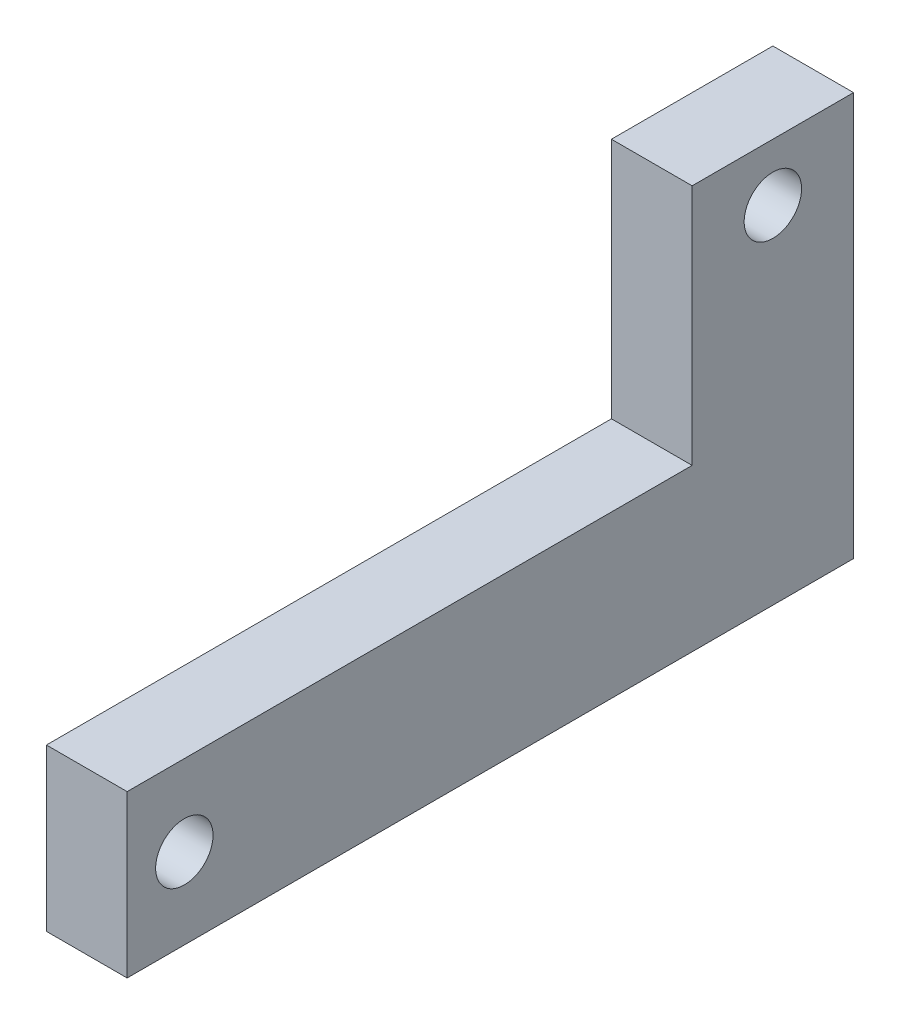
SolidWorks part; units mm, degrees
ref_plane "Front Plane" through (0, 0, 0) normal (0, 0, 1) x (1, 0, 0)
ref_plane "Top Plane" through (0, 0, 0) normal (0, 1, 0) x (1, 0, 0)
ref_plane "Right Plane" through (0, 0, 0) normal (1, 0, 0) x (0, 0, -1)
sketch "Sketch1" plane through (0, 0, 0) normal (1, 0, 0) x (0, 0, -1)
  line L0 (-40, -7.5) -> (5, -7.5) construction
  line L1 (-40, -2.5) -> (-5, -2.5)
  line L2 (-40, -2.5) -> (-40, -12.5)
  line L3 (-40, -12.5) -> (5, -12.5)
  line L4 (5, -2.5) -> (5, -12.5)
  line L6 (5, -2.5) -> (5, 12.5)
  line L7 (5, 12.5) -> (-5, 12.5)
  line L8 (-5, -2.5) -> (-5, 12.5)
  line L9 (0, 12.5) -> (0, -12.5) construction
  line L10 (-51.9371, -2.5) -> (-51.9371, -12.5) construction
  point P16 (-51.9371, -7.5)
  dimension "D1" = 45
  dimension "D2" = 10
  dimension "D3" = 10
  dimension "D4" = 25
extrude "Boss-Extrude1" add sketch "Sketch1" along normal blind 5
hole_wizard "5/32 (0.14) Diameter Hole1" positions "Sketch2" profile "Sketch3" hole size "5/32" standard "ANSI Inch" end condition through all
sketch "Sketch2" plane through (5, 0, 0) normal (1, 0, 0) x (0, 0, -1)
  line L0 (-40, -2.5) -> (-40, -12.5) construction
  line L1 (5, 12.5) -> (-5, 12.5) construction
  line L2 (-36.4575, -7.5) -> (-40, -7.5) construction
  line L4 (0, 8.9575) -> (0, 12.5) construction
  point P0 (0, 8.9575)
  point P2 (-36.4575, -7.5)
  point P7 (-40, -7.5)
  point P10 (0, 12.5)
  dimension "D1" = 40
sketch "Sketch3" plane through (5, 8.9575, 0) normal (0, 1, 0) x (0, 0, -1)
  line L0 (0, 0) -> (0, 5)
  line L1 (0, 5) -> (1.778, 5)
  line L2 (1.778, 5) -> (1.778, 0)
  line L5 (1.778, 0) -> (0, 0)
  line L11 (0, -6.35) -> (0, 107.95) construction
  dimension "Thru Hole Dia." = 3.556
  dimension "Thru Hole Depth" = 5
